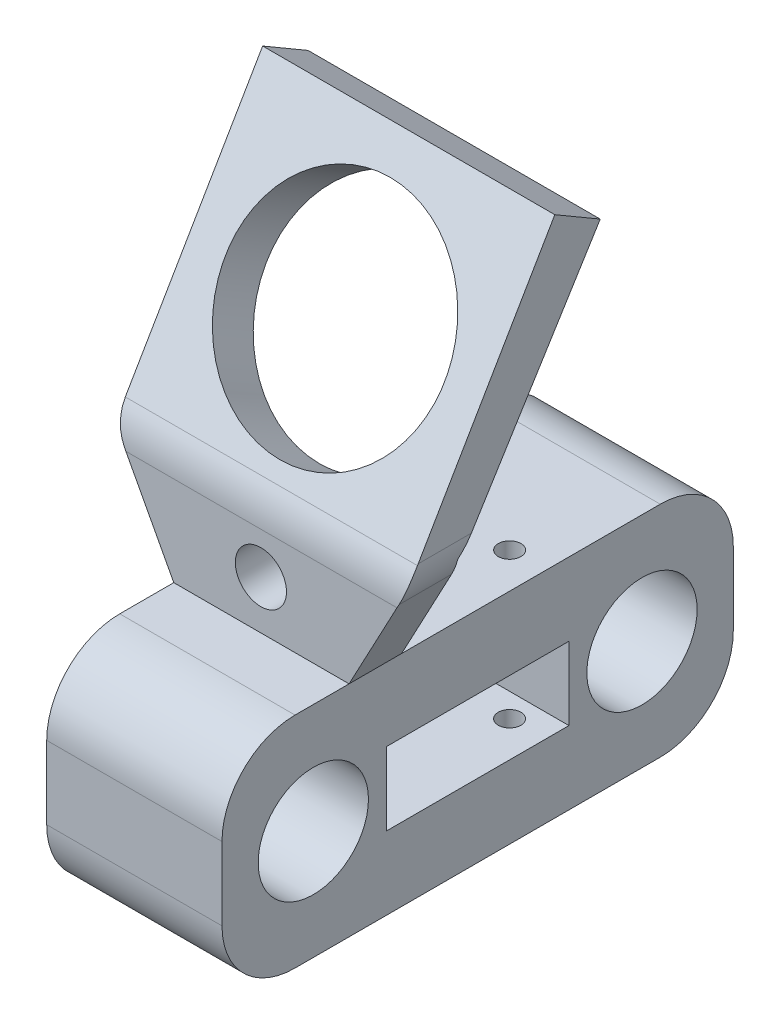
SolidWorks part; units mm, degrees
ref_plane "前视基准面" through (0, 0, 0) normal (0, 0, 1) x (1, 0, 0)
ref_plane "上视基准面" through (0, 0, 0) normal (0, 1, 0) x (1, 0, 0)
ref_plane "右视基准面" through (0, 0, 0) normal (1, 0, 0) x (0, 0, -1)
sketch "草图1" plane through (0, 0, 0) normal (0, 1, 0) x (1, 0, 0)
  line L1 (8.2419, 10.5227) -> (32.2419, 10.5227)
  line L2 (8.2419, 10.5227) -> (8.2419, -59.4773)
  line L3 (8.2419, -59.4773) -> (32.2419, -59.4773)
  line L4 (32.2419, 10.5227) -> (32.2419, -59.4773)
  line L5 (8.2419, 10.5227) -> (32.2419, -59.4773) construction
  line L6 (8.2419, -59.4773) -> (32.2419, 10.5227) construction
  point P4 (20.2419, -24.4773)
  dimension "D1" = 24
  dimension "D2" = 70
extrude "凸台-拉伸1" add sketch "草图1" along normal blind 30
sketch "草图2" plane through (32.2419, 0, 0) normal (1, 0, 0) x (0, 0, -1)
  line L0 (-24.4773, 0) -> (-24.4773, 30) construction
  line L1 (-59.4773, 0) -> (10.5227, 0) construction
  line L2 (-59.4773, 30) -> (10.5227, 30) construction
  line L3 (-59.4773, 15) -> (10.5227, 15) construction
  line L4 (-59.4773, 30) -> (-59.4773, 0) construction
  line L5 (10.5227, 30) -> (10.5227, 0) construction
  circle A0 centre (-46.9773, 15) radius 7.55
  circle A1 centre (-1.9773, 15) radius 7.55
  dimension "D1" = 15.1
  dimension "D3" = 12.5
  dimension "D2" = 45
extrude "切除-拉伸1" cut sketch "草图2" against normal through all
sketch "草图3" plane through (32.2419, 0, 0) normal (1, 0, 0) x (0, 0, -1)
  line L1 (-36.9773, 20) -> (-11.9773, 20)
  line L2 (-36.9773, 20) -> (-36.9773, 10)
  line L3 (-36.9773, 10) -> (-11.9773, 10)
  line L4 (-11.9773, 20) -> (-11.9773, 10)
  line L5 (-36.9773, 20) -> (-11.9773, 10) construction
  line L6 (-36.9773, 10) -> (-11.9773, 20) construction
  point P4 (-24.4773, 15)
extrude "切除-拉伸2" cut sketch "草图3" against normal through all
sketch "草图4" plane through (0, 30, 0) normal (0, 1, 0) x (1, 0, 0)
  line L0 (8.2419, -12.6108) -> (8.2419, -21.9283)
  line L1 (8.2419, 10.5227) -> (8.2419, -59.4773) construction
  line L2 (8.2419, -21.9283) -> (32.2419, -21.9283)
  line L3 (32.2419, -59.4773) -> (32.2419, 10.5227) construction
  line L4 (32.2419, -21.9283) -> (32.2419, -12.6108)
  line L5 (32.2419, -12.6108) -> (8.2419, -12.6108)
fillet "圆角1" radius 10 4 edges at (20.2419, 0, 59.4773) (20.2419, 30, 59.4773) (20.2419, 0, -10.5227) (20.2419, 30, -10.5227)
sketch "草图6" plane through (0, 30, 0) normal (0, 1, 0) x (1, 0, 0)
  line L0 (32.2419, -49.4773) -> (32.2419, 0.5227) construction
  line L1 (32.2419, -42.0808) -> (8.2419, -42.0808)
  line L2 (32.2419, -42.0808) -> (32.2419, -34.8822)
  line L3 (32.2419, -34.8822) -> (8.2419, -34.8822)
  line L4 (8.2419, -42.0808) -> (8.2419, -34.8822)
  line L5 (32.2419, -42.0808) -> (8.2419, -34.8822) construction
  line L6 (32.2419, -34.8822) -> (8.2419, -42.0808) construction
  line L7 (8.2419, 0.5227) -> (8.2419, -49.4773) construction
  point P4 (20.2419, -38.4815)
extrude "凸台-拉伸3" add sketch "草图6" along normal blind 15
sketch "草图7" plane through (8.2419, 0, 0) normal (-1, 0, 0) x (0, 0, 1)
  line L1 (42.0808, 45) -> (21.9126, 79.5433)
  line L2 (21.9126, 79.5433) -> (15.6948, 75.9131)
  line L3 (15.6948, 75.9131) -> (34.8822, 45)
  line L4 (34.8822, 45) -> (42.0808, 45)
  dimension "D1" = 7.2
  dimension "D2" = 40
extrude "凸台-拉伸4" add sketch "草图7" against normal up to surface (24 mm away) up to face at (32.2419, 15, 24.4773)
sketch "草图8" plane through (8.2419, 0, 0) normal (-1, 0, 0) x (0, 0, 1)
  line L0 (42.0808, 45) -> (34.8822, 45)
  line L1 (34.8822, 45) -> (15.6948, 75.9131)
  line L2 (15.6948, 75.9131) -> (21.9126, 79.5433)
  line L3 (21.9126, 79.5433) -> (42.0808, 45)
extrude "凸台-拉伸5" add sketch "草图8" along normal blind 8
sketch "草图9" plane through (32.2419, 0, 0) normal (1, 0, 0) x (0, 0, -1)
  line L1 (-42.0808, 45) -> (-34.8822, 45)
  line L2 (-34.8822, 45) -> (-15.6948, 75.9131)
  line L3 (-15.6948, 75.9131) -> (-21.9126, 79.5433)
  line L4 (-21.9126, 79.5433) -> (-42.0808, 45)
extrude "凸台-拉伸6" add sketch "草图9" along normal blind 8
sketch "草图10" plane through (0, 29.7631, 50.977) normal (0, 0.5042, 0.8636) x (1, 0, 0)
  line L0 (40.2419, 37.6439) -> (0.2419, 37.6439) construction
  line L1 (40.2419, 57.6439) -> (40.2419, 17.6439) construction
  line L2 (0.2419, 17.6439) -> (0.2419, 57.6439) construction
  circle A0 centre (20.2419, 37.6439) radius 15
  dimension "D1" = 30
extrude "切除-拉伸4" cut sketch "草图10" against normal blind 16
ref_plane "基准面1" through (0.2419, 45, 42.0808) normal (1, 0, 0) x (0, 0, -1)
sketch "草图12" plane through (0, 0, 42.0808) normal (0, 0, 1) x (1, 0, 0)
  line L1 (0.2419, 45) -> (8.2419, 45)
  line L2 (8.2419, 45) -> (8.2419, 30)
  line L3 (8.2419, 30) -> (0.2419, 45)
extrude "凸台-拉伸7" add sketch "草图12" against normal up to surface (7.1986 mm away) up to face at (20.2419, 37.5, 34.8822)
sketch "草图13" plane through (0, 0, 42.0808) normal (0, 0, 1) x (1, 0, 0)
  line L1 (40.2419, 45) -> (32.2419, 45)
  line L2 (32.2419, 45) -> (32.2419, 30)
  line L3 (32.2419, 30) -> (40.2419, 45)
extrude "凸台-拉伸8" add sketch "草图13" against normal up to surface (7.1986 mm away) up to face at (18.2419, 37.5, 34.8822)
fillet "圆角2" radius 10 1 edges at (20.2419, 45, 42.0808)
fillet "圆角3" radius 10 2 edges at (0.2419, 45, 38.295) (40.2419, 45, 38.295)
sketch "草图14" plane through (0, 0, 42.0808) normal (0, 0, 1) x (1, 0, 0)
  circle A0 centre (20.1704, 36.6171) radius 3.5
  dimension "D1" = 7
extrude "切除-拉伸5" cut sketch "草图14" against normal blind 13
sketch "草图16" plane through (0, 30, 0) normal (0, 1, 0) x (1, 0, 0)
  circle A0 centre (13.07, -15.2289) radius 1.6
  circle A1 centre (27.37, -15.2289) radius 1.5505
extrude "切除-拉伸6" cut sketch "草图16" against normal blind 26
